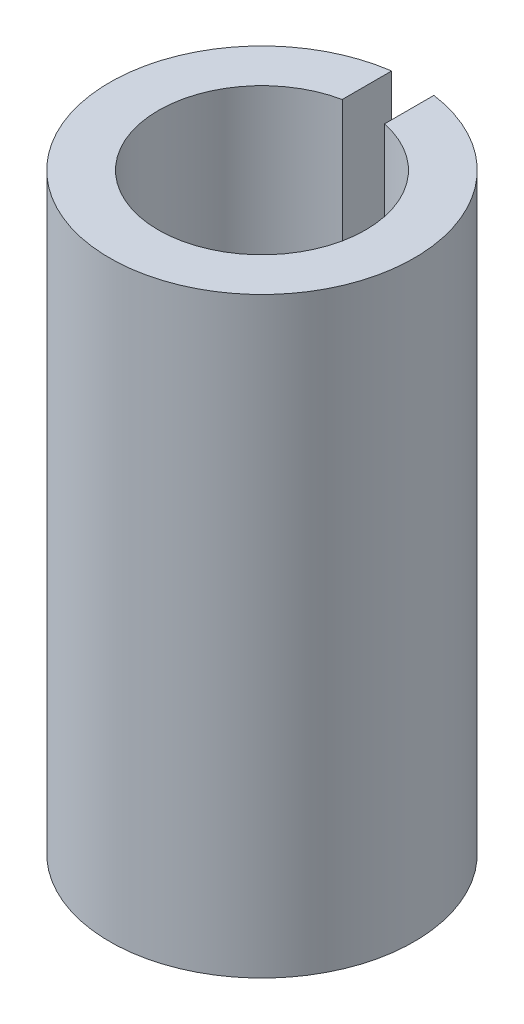
SolidWorks part; units mm, degrees
ref_plane "前视基准面" through (0, 0, 0) normal (0, 0, 1) x (1, 0, 0)
ref_plane "上视基准面" through (0, 0, 0) normal (0, 1, 0) x (1, 0, 0)
ref_plane "右视基准面" through (0, 0, 0) normal (1, 0, 0) x (0, 0, -1)
sketch "草图1" plane through (0, 0, 0) normal (0, 1, 0) x (1, 0, 0)
  circle A0 centre (0, 0) radius 1.8
  circle A1 centre (0, 0) radius 1.225
  dimension "D1" = 3.6
  dimension "D2" = 2.45
extrude "凸台-拉伸1" add sketch "草图1" along normal blind 7
sketch "草图2" plane through (0, 7, 0) normal (0, 1, 0) x (1, 0, 0)
  line L1 (-0.25, 2.9881) -> (0.25, 2.9881)
  line L2 (-0.25, 2.9881) -> (-0.25, 0.6119)
  line L3 (-0.25, 0.6119) -> (0.25, 0.6119)
  line L4 (0.25, 2.9881) -> (0.25, 0.6119)
  line L5 (-0.25, 2.9881) -> (0.25, 0.6119) construction
  line L6 (-0.25, 0.6119) -> (0.25, 2.9881) construction
  circle A0 centre (0, 0) radius 1.8 construction
  point P0 (0, 1.8)
  dimension "D1" = 0.5
extrude "切除-拉伸1" cut sketch "草图2" against normal through all
